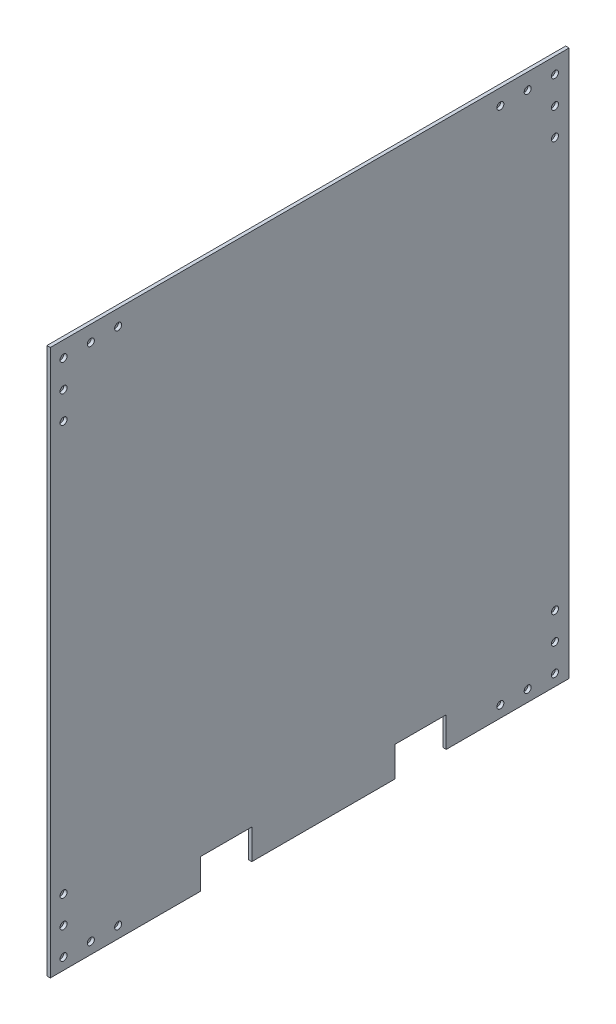
SolidWorks part; units mm, degrees
ref_plane "Front Plane" through (0, 0, 0) normal (0, 0, 1) x (1, 0, 0)
ref_plane "Top Plane" through (0, 0, 0) normal (0, 1, 0) x (1, 0, 0)
ref_plane "Right Plane" through (0, 0, 0) normal (1, 0, 0) x (0, 0, -1)
sketch "Sketch1" plane through (0, 0, 0) normal (1, 0, 0) x (0, 0, -1)
  line L1 (557.8339, -12.6915) -> (1040.4339, -12.6915)
  line L2 (557.8339, -12.6915) -> (557.8339, -520.6915)
  line L3 (557.8339, -520.6915) -> (1040.4339, -520.6915)
  line L4 (1040.4339, -12.6915) -> (1040.4339, -520.6915)
  dimension "D1" = 482.6
  dimension "D2" = 508
extrude "Boss-Extrude1" add sketch "Sketch1" along normal blind 3.175
sketch "Sketch2" plane through (3.175, 0, 0) normal (1, 0, 0) x (0, 0, -1)
  line L0 (557.8339, -520.6915) -> (1040.4339, -520.6915) construction
  line L1 (697.5339, -520.6915) -> (745.2859, -520.6915)
  line L2 (697.5339, -520.6915) -> (697.5339, -492.7515)
  line L3 (697.5339, -492.7515) -> (745.2859, -492.7515)
  line L4 (745.2859, -520.6915) -> (745.2859, -492.7515)
  line L5 (1040.4339, -520.6915) -> (1040.4339, -12.6915) construction
  line L6 (878.3819, -520.6915) -> (926.1339, -520.6915)
  line L7 (878.3819, -520.6915) -> (878.3819, -492.7515)
  line L8 (878.3819, -492.7515) -> (926.1339, -492.7515)
  line L9 (926.1339, -520.6915) -> (926.1339, -492.7515)
  line L10 (557.8339, -12.6915) -> (557.8339, -520.6915) construction
  dimension "D1" = 47.752
  dimension "D2" = 27.94
  dimension "D3" = 114.3
  dimension "D4" = 47.752
  dimension "D5" = 27.94
  dimension "D6" = 139.7
extrude "Cut-Extrude1" cut sketch "Sketch2" against normal through all
sketch "Sketch3" plane through (3.175, 0, 0) normal (1, 0, 0) x (0, 0, -1)
  circle A0 centre (570.1168, -27.3994) radius 3.2639
  circle A1 centre (595.5168, -27.3994) radius 3.2639
  circle A2 centre (620.9168, -27.3994) radius 3.2639
  circle A3 centre (570.1168, -52.7994) radius 3.2639
  circle A4 centre (570.1168, -78.1994) radius 3.2639
  circle A5 centre (570.1168, -509.9994) radius 3.2639
  circle A6 centre (570.1168, -484.5994) radius 3.2639
  circle A7 centre (570.1168, -459.1994) radius 3.2639
  circle A8 centre (595.5168, -509.9994) radius 3.2639
  circle A9 centre (620.9168, -509.9994) radius 3.2639
  circle A10 centre (1027.3168, -509.9994) radius 3.2639
  circle A11 centre (1001.9168, -509.9994) radius 3.2639
  circle A12 centre (976.5168, -509.9994) radius 3.2639
  circle A13 centre (1027.3168, -459.1994) radius 3.2639
  circle A14 centre (1027.3168, -484.5994) radius 3.2639
  circle A15 centre (1027.3168, -27.3994) radius 3.2639
  circle A16 centre (1001.9168, -27.3994) radius 3.2639
  circle A17 centre (976.5168, -27.3994) radius 3.2639
  circle A18 centre (1027.3168, -52.7994) radius 3.2639
  circle A19 centre (1027.3168, -78.1994) radius 3.2639
extrude "Cut-Extrude2" cut sketch "Sketch3" against normal blind 3
